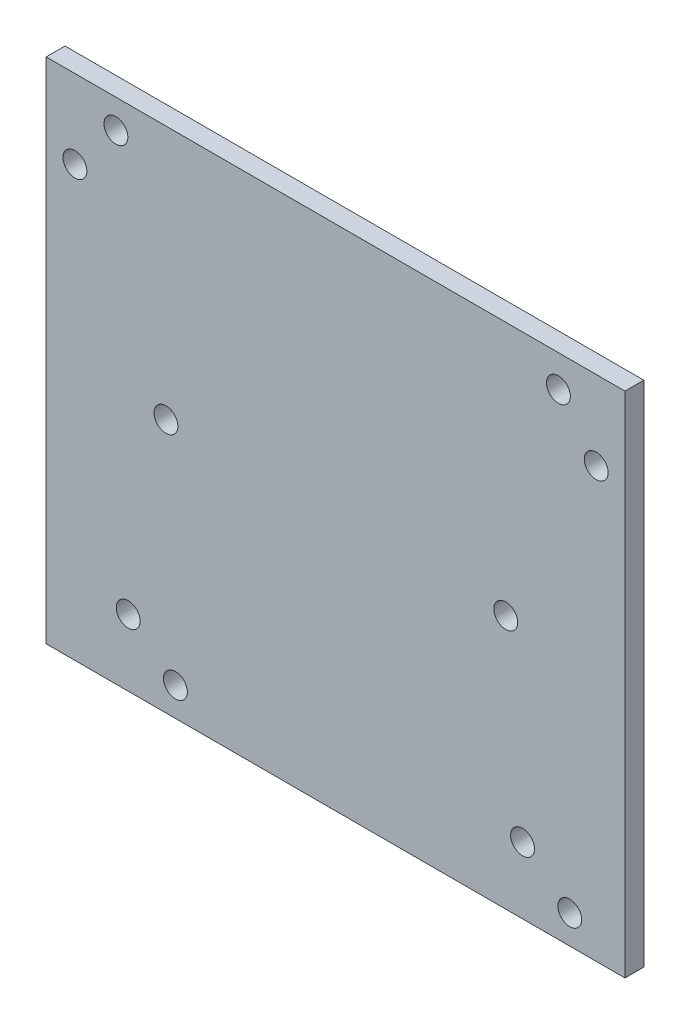
SolidWorks part; units mm, degrees
ref_plane "Front Plane" through (0, 0, 0) normal (0, 0, 1) x (1, 0, 0)
ref_plane "Top Plane" through (0, 0, 0) normal (0, 1, 0) x (1, 0, 0)
ref_plane "Right Plane" through (0, 0, 0) normal (1, 0, 0) x (0, 0, -1)
sketch "Sketch1" plane through (0, 0, 0) normal (0, 0, 1) x (1, 0, 0)
  line L0 (959.4886, 308.695) -> (959.4886, 257.3944) construction
  line L1 (959.4886, 234.6614) -> (959.4886, 406.5207) construction
  line L2 (862.0448, 217.2783) -> (1056.7178, 217.2783)
  line L3 (862.0448, 217.2783) -> (862.0448, 388.2332)
  line L4 (862.0448, 388.2332) -> (1056.7178, 388.2332)
  line L5 (1056.7178, 217.2783) -> (1056.7178, 388.2332)
  line L6 (902.3386, 302.7557) -> (1016.6386, 302.7557) construction
  circle A0 centre (1022.28, 239.6533) radius 2.5273 construction
  circle A1 centre (1038.155, 226.9533) radius 2.5273 construction
  circle A2 centre (889.6448, 239.6533) radius 2.5273 construction
  circle A3 centre (1034.3339, 377.4809) radius 2.5273 construction
  circle A4 centre (1047.0428, 361.6131) radius 2.5273 construction
  circle A5 centre (871.7198, 361.7933) radius 2.5273 construction
  circle A6 centre (885.5053, 378.5582) radius 2.5273 construction
  circle A7 centre (1022.28, 239.6533) radius 2.5273 construction
  circle A8 centre (1038.155, 226.9533) radius 2.5273 construction
  circle A9 centre (889.6448, 239.6533) radius 2.5273 construction
  circle A10 centre (1034.3339, 377.4809) radius 2.5273 construction
  circle A11 centre (1047.0428, 361.6131) radius 2.5273 construction
  circle A12 centre (871.7198, 361.7933) radius 2.5273 construction
  circle A13 centre (885.5053, 378.5582) radius 2.5273 construction
  circle A14 centre (905.5198, 226.9533) radius 2.5273 construction
  circle A15 centre (905.5198, 226.9533) radius 2.5273 construction
  circle A16 centre (1022.28, 239.6533) radius 4.0127
  circle A17 centre (1038.155, 226.9533) radius 4.0127
  circle A18 centre (889.6448, 239.6533) radius 4.0127
  circle A19 centre (1034.3339, 377.4809) radius 4.0127
  circle A20 centre (1047.0428, 361.6131) radius 4.0127
  circle A21 centre (871.7198, 361.7933) radius 4.0127
  circle A22 centre (885.5053, 378.5582) radius 4.0127
  circle A23 centre (905.5198, 226.9533) radius 4.0127
  circle A24 centre (885.5053, 378.5582) radius 6.5 construction
  circle A25 centre (871.7198, 361.7933) radius 6.5 construction
  circle A26 centre (889.6448, 239.6533) radius 6.5 construction
  circle A27 centre (905.5198, 226.9533) radius 6.5 construction
  circle A28 centre (1022.28, 239.6533) radius 6.5 construction
  circle A29 centre (1038.155, 226.9533) radius 6.5 construction
  circle A30 centre (1047.0428, 361.6131) radius 6.5 construction
  circle A31 centre (1034.3339, 377.4809) radius 6.5 construction
  circle A32 centre (-682.1218, 370.9328) radius 4.0127 construction
  circle A33 centre (902.3386, 302.7557) radius 4.0127
  circle A34 centre (-672.6612, 269.9726) radius 4.0132 construction
  circle A35 centre (-672.6612, 269.9726) radius 4.0132 construction
  circle A36 centre (1016.6386, 302.7557) radius 4.0127
  point P60 (959.4886, 302.7557)
  point P76 (862.0448, 302.7557)
  dimension "D2" = 114.3
  dimension "D1" = 13
  dimension "D3" = 3.175
  dimension "D4" = 3.175
  dimension "D5" = 3.175
  dimension "D6" = 3.175
extrude "Boss-Extrude1" add sketch "Sketch1" along normal blind 6.35
